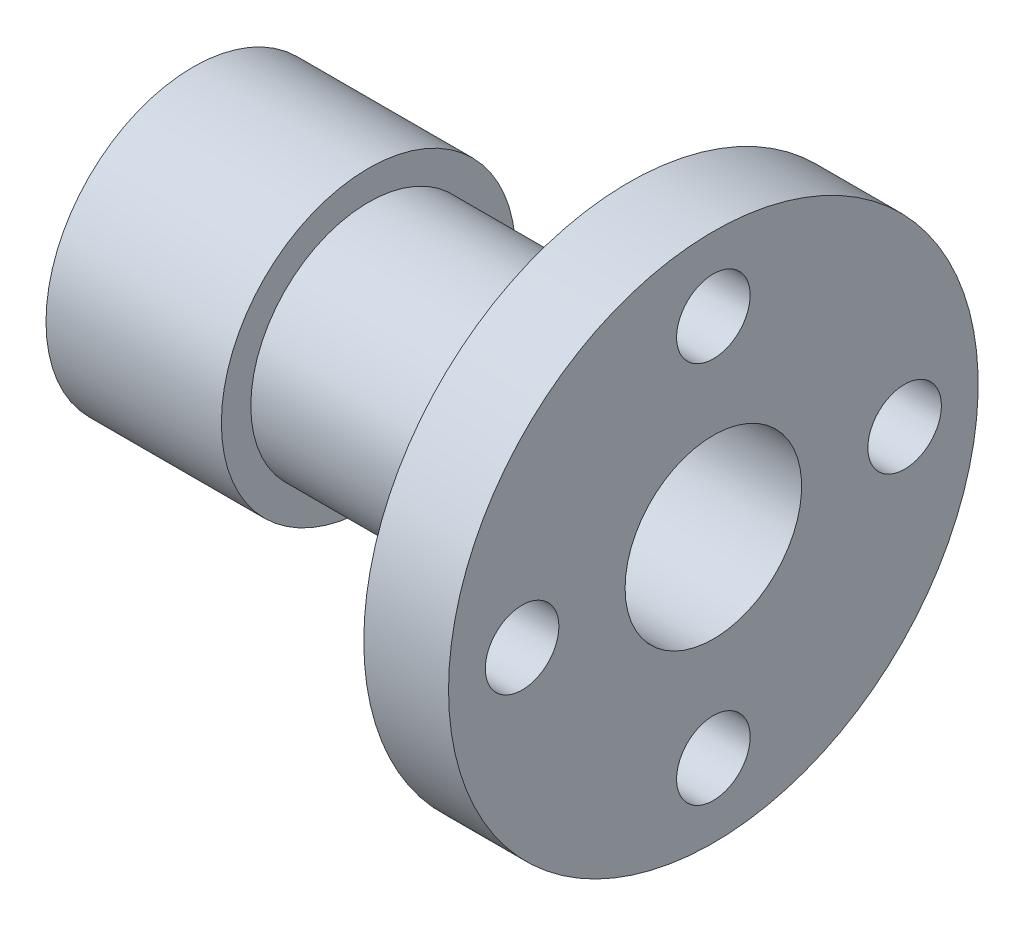
SolidWorks part; units mm, degrees
material "Thornel Mat VMA"
ref_plane "Front Plane" through (0, 0, 0) normal (0, 0, 1) x (1, 0, 0)
ref_plane "Top Plane" through (0, 0, 0) normal (0, 1, 0) x (1, 0, 0)
ref_plane "Right Plane" through (0, 0, 0) normal (1, 0, 0) x (0, 0, -1)
sketch "Sketch1" plane through (0, 0, 0) normal (0, 1, 0) x (1, 0, 0)
  line L0 (-44.2, 0) -> (44.2, 0) construction
  line L1 (-44.2, 25) -> (-14.4, 25)
  line L2 (-14.4, 25) -> (-14.4, 20)
  line L3 (-14.4, 20) -> (29.8, 20)
  line L4 (29.8, 20) -> (29.8, 45)
  line L5 (29.8, 45) -> (44.2, 45)
  line L6 (44.2, 45) -> (44.2, 15)
  line L9 (20.4, 15) -> (-20.4, 15)
  line L10 (-20.4, 15) -> (-20.2, 19)
  line L11 (-20.2, 19) -> (-44.2, 19)
  line L12 (-44.2, 19) -> (-44.2, 25)
  line L13 (20.4, 15) -> (44.2, 15)
  point P3 (0, 0)
  point P10 (0, 15)
  dimension "D2" = 14.4
  dimension "D4" = 44.2
  dimension "D5" = 6
  dimension "D6" = 24
  dimension "D8" = 15
  dimension "D9" = 20
  dimension "D10" = 19
  dimension "D11" = 25
revolve "Revolve1" add sketch "Sketch1" angle 360 about L0
sketch "Sketch2" plane through (44.2, 0, 0) normal (1, 0, 0) x (0, 0, -1)
  line L0 (0, 45) -> (0, -45) construction
  line L1 (-45, 0) -> (45, 0) construction
  circle A0 centre (0, 0) radius 45 construction
  circle A1 centre (0, 32.5) radius 6.25
  circle A2 centre (32.5, 0) radius 6.25
  circle A3 centre (0, -32.5) radius 6.25
  circle A4 centre (-32.5, 0) radius 6.25
  point P9 (0, 0)
  point P19 (0, 0)
  dimension "D1" = 12.5
  dimension "D2" = 32.5
  dimension "D3" = 4
extrude "Cut-Extrude1" cut sketch "Sketch2" against normal through all
